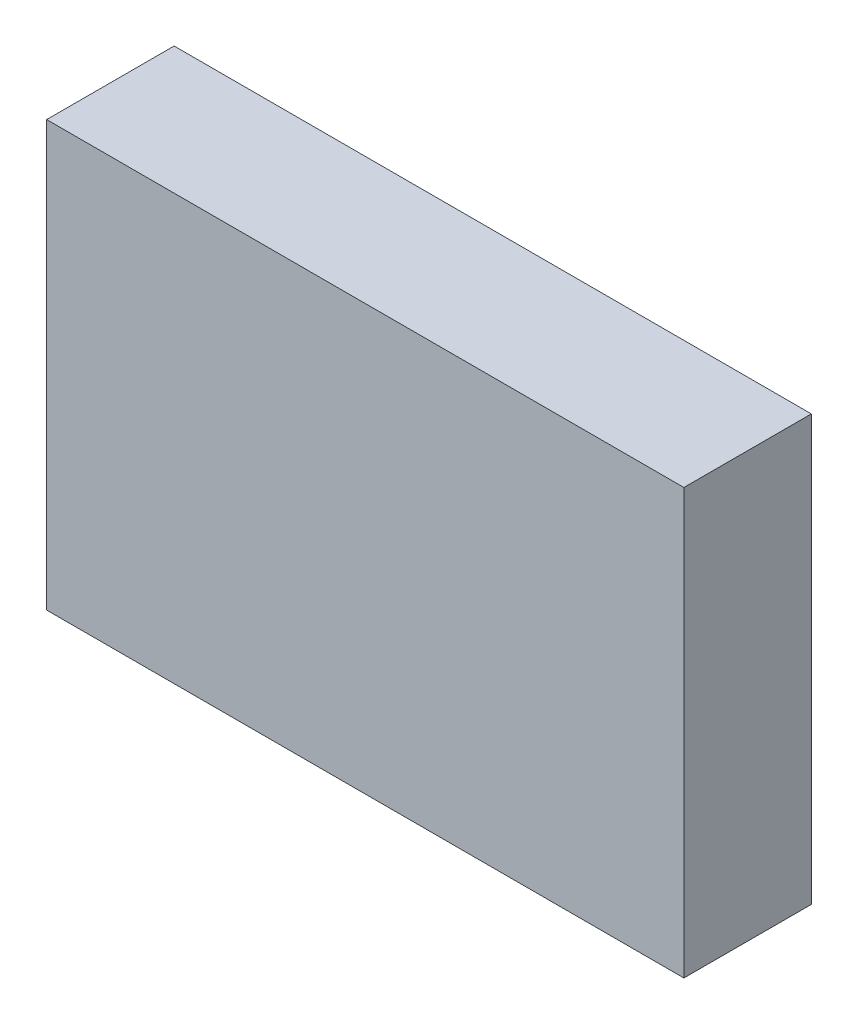
SolidWorks part; units mm, degrees
ref_plane "Front" through (0, 0, 0) normal (0, 0, 1) x (1, 0, 0)
ref_plane "Top" through (0, 0, 0) normal (0, 1, 0) x (1, 0, 0)
ref_plane "Right" through (0, 0, 0) normal (1, 0, 0) x (0, 0, -1)
sketch "草图1" plane through (0, 0, 0) normal (0, 0, 1) x (1, 0, 0)
  line L1 (-21.2547, 5.0619) -> (8.7453, 5.0619)
  line L2 (-21.2547, 5.0619) -> (-21.2547, -14.9381)
  line L3 (-21.2547, -14.9381) -> (8.7453, -14.9381)
  line L4 (8.7453, 5.0619) -> (8.7453, -14.9381)
extrude "凸台-拉伸1" add sketch "草图1" along normal blind 6
